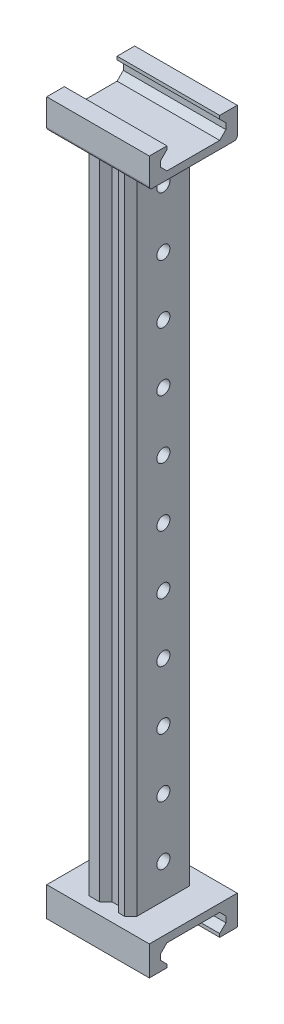
SolidWorks part; units mm, degrees
ref_plane "Front Plane" through (0, 0, 0) normal (1, 0, 0) x (0, 1, 0)
ref_plane "Top Plane" through (0, 0, 0) normal (0, 0, 1) x (0, 1, 0)
ref_plane "Right Plane" through (0, 0, 0) normal (0, 1, 0) x (-1, 0, 0)
sketch "Sketch1" plane through (0, 0, 0) normal (1, 0, 0) x (0, 1, 0)
  line L0 (60.1161, 26.3922) -> (61.2508, 26.3922)
  line L1 (60.1161, 8.3892) -> (61.2508, 8.3892)
  line L2 (53.8622, 26.3922) -> (53.8622, 8.3892)
  line L3 (53.8622, 8.3892) -> (55.9854, 6.266)
  line L4 (55.9854, 6.266) -> (57.9929, 6.266)
  line L5 (57.9929, 6.266) -> (60.1161, 8.3892)
  line L12 (53.8622, 17.3907) -> (73.2887, 17.3907) construction
  line L20 (57.9929, 28.5154) -> (60.1161, 26.3922)
  line L21 (55.9854, 28.5154) -> (57.9929, 28.5154)
  line L22 (53.8622, 26.3922) -> (55.9854, 28.5154)
  line L23 (61.2508, 26.3922) -> (61.2508, 32.3922)
  line L24 (61.2508, 32.3922) -> (51.1805, 32.3922)
  line L25 (51.1805, 32.3922) -> (51.1805, 2.3892)
  line L26 (51.1805, 2.3892) -> (61.2508, 2.3892)
  line L27 (61.2508, 2.3892) -> (61.2508, 8.3892)
extrude "Boss-Extrude1" add sketch "Sketch1" along normal blind 35
ref_plane "Plane2" through (0, -60.1778, 0) normal (0, 1, 0) x (1, 0, 0)
mirror "Mirror4" about plane through (0, -60.1778, 0) normal (0, 1, 0) of bodies 101
fillet "Fillet1" radius 1 2 edges at (17.5, 51.1805, 2.3892) (17.5, 51.1805, 32.3922)
sketch "Sketch3" plane through (0, 51.1805, 0) normal (0, -1, 0) x (1, 0, 0)
  line L2 (24.7331, 8.3338) -> (24.7331, 26.3367)
  line L3 (24.7331, 26.3367) -> (22.6099, 28.46)
  line L4 (22.6099, 28.46) -> (20.6024, 28.46)
  line L5 (20.6024, 28.46) -> (18.4792, 26.3367)
  line L6 (18.4792, 26.3367) -> (16.2097, 26.3367)
  line L7 (16.2097, 26.3367) -> (14.0865, 28.46)
  line L8 (14.0865, 28.46) -> (10.508, 28.46)
  line L9 (10.508, 28.46) -> (9.4464, 27.3983)
  line L10 (9.4464, 27.3983) -> (9.4464, 19.5734)
  line L11 (9.4464, 19.5734) -> (10.508, 18.5118)
  line L12 (7.3066, 17.3353) -> (26.7331, 17.3353) construction
  line L13 (10.508, 18.5118) -> (10.508, 16.1587)
  line L14 (9.4464, 15.0971) -> (10.508, 16.1587)
  line L15 (9.4464, 7.2722) -> (9.4464, 15.0971)
  line L16 (10.508, 6.2106) -> (9.4464, 7.2722)
  line L17 (14.0865, 6.2106) -> (10.508, 6.2106)
  line L18 (16.2097, 8.3338) -> (14.0865, 6.2106)
  line L19 (18.4792, 8.3338) -> (16.2097, 8.3338)
  line L20 (20.6024, 6.2106) -> (18.4792, 8.3338)
  line L21 (22.6099, 6.2106) -> (20.6024, 6.2106)
  line L22 (24.7331, 8.3338) -> (22.6099, 6.2106)
  line L23 (35, 17.3907) -> (0, 17.3907) construction
  line L24 (35, 31.3922) -> (35, 3.3892) construction
  line L25 (0, 31.3922) -> (0, 3.3892) construction
  point P17 (10.508, 17.3353)
extrude "Boss-Extrude2" add sketch "Sketch3" along normal up to surface (222.7166 mm away) up to face at (17.5, -171.5361, 17.3907)
sketch "Sketch6" plane through (9.4464, 0, 0) normal (-1, 0, 0) x (0, -1, 0)
  circle A0 centre (159.829, 17.3353) radius 2.2382
  circle A1 centre (139.829, 17.3353) radius 2.2382
  circle A2 centre (119.829, 17.3353) radius 2.2382
  circle A3 centre (99.829, 17.3353) radius 2.2382
  circle A4 centre (79.829, 17.3353) radius 2.2382
  circle A5 centre (59.829, 17.3353) radius 2.2382
  circle A6 centre (39.829, 17.3353) radius 2.2382
  circle A7 centre (19.829, 17.3353) radius 2.2382
  circle A8 centre (-0.171, 17.3353) radius 2.2382
  circle A9 centre (-20.171, 17.3353) radius 2.2382
  circle A10 centre (-40.171, 17.3353) radius 2.2382
  dimension "D1" = 11
extrude "Cut-Extrude1" cut sketch "Sketch6" against normal up to surface (15.2867 mm away) up to face at (24.7331, -60.1778, 17.3353)
